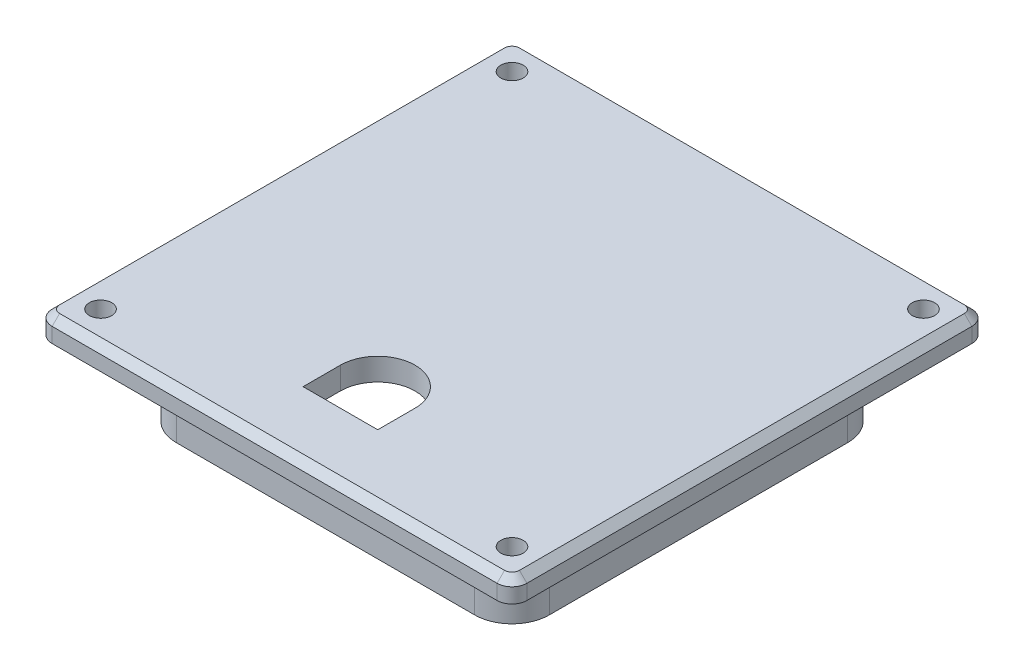
SolidWorks part; units mm, degrees
ref_plane "Front Plane" through (0, 0, 0) normal (0, 0, 1) x (1, 0, 0)
ref_plane "Top Plane" through (0, 0, 0) normal (0, 1, 0) x (1, 0, 0)
ref_plane "Right Plane" through (0, 0, 0) normal (1, 0, 0) x (0, 0, -1)
sketch "Sketch1" plane through (0, 0, 0) normal (0, 1, 0) x (1, 0, 0)
  line L1 (-25, 25) -> (25, 25)
  line L2 (-25, 25) -> (-25, -25)
  line L3 (-25, -25) -> (25, -25)
  line L4 (25, 25) -> (25, -25)
  line L5 (-23, 23) -> (23, 23)
  line L6 (-23, 23) -> (-23, -23)
  line L7 (-23, -23) -> (23, -23)
  line L8 (23, 23) -> (23, -23)
  circle A0 centre (0, 0) radius 25 construction
  circle A1 centre (0, 0) radius 23 construction
  dimension "D1" = 50
  dimension "D2" = 46
extrude "Boss-Extrude1" add sketch "Sketch1" along normal blind 10
sketch "Sketch2" plane through (0, 10, 0) normal (0, 1, 0) x (1, 0, 0)
  line L3 (-5, -23) -> (5, -23)
  line L6 (-27.5772, 27.5772) -> (0, 0) construction
  line L7 (0, 0) -> (39, 0) construction
  line L8 (-27.5772, -27.5772) -> (0, 0) construction
  line L9 (0, 0) -> (27.5772, -27.5772) construction
  line L10 (0, 0) -> (27.5772, 27.5772) construction
  line L11 (-27.5772, 27.5772) -> (-31.8198, 31.8198) construction
  line L12 (0, -23) -> (0, -13) construction
  line L13 (-31.8198, 31.8198) -> (31.8198, 31.8198)
  line L14 (-31.8198, 31.8198) -> (-31.8198, -31.8198)
  line L15 (-31.8198, -31.8198) -> (31.8198, -31.8198)
  line L16 (31.8198, 31.8198) -> (31.8198, -31.8198)
  line L17 (-5, -18) -> (-5, -23)
  line L18 (5, -18) -> (5, -23)
  circle A0 centre (0, 0) radius 45 construction
  circle A1 centre (0, 0) radius 39 construction
  circle A2 centre (-27.5772, 27.5772) radius 1.5
  circle A3 centre (27.5772, 27.5772) radius 1.5
  circle A4 centre (-27.5772, -27.5772) radius 1.5
  circle A5 centre (27.5772, -27.5772) radius 1.5
  arc A6 (5, -18) -> (-5, -18) centre (0, -18) ccw
  dimension "D1" = 78
  dimension "D2" = 90
  dimension "D7" = 3
  dimension "D3" = 45
  dimension "D4" = 90
  dimension "D5" = 45
  dimension "D6" = 90
  dimension "D8" = 10
extrude "Boss-Extrude2" add sketch "Sketch2" along normal blind 3
fillet "Fillet2" radius 5 4 edges at (-25, 5, 25) (25, 5, 25) (25, 5, -25) (-25, 5, -25)
fillet "Fillet3" radius 2 4 edges at (31.8198, 11.5, -31.8198) (-31.8198, 11.5, -31.8198) (-31.8198, 11.5, 31.8198) (31.8198, 11.5, 31.8198)
chamfer "Chamfer2" distance 1 angle 45 8 edges at (31.8198, 13, 0) (31.234, 13, -31.234) (31.234, 13, 31.234) (0, 13, -31.8198) (0, 13, 31.8198) (-31.234, 13, -31.234) (-31.234, 13, 31.234) (-31.8198, 13, 0)
